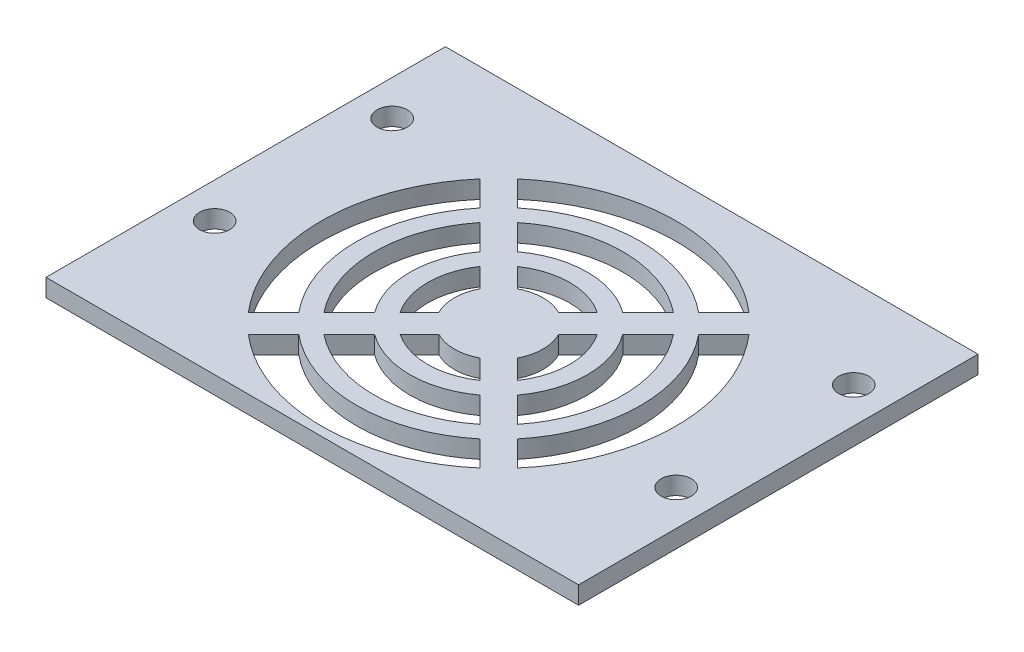
SolidWorks part; units mm, degrees
material "ABS PC"
ref_plane "Front Plane" through (0, 0, 0) normal (0, 0, 1) x (1, 0, 0)
ref_plane "Top Plane" through (0, 0, 0) normal (0, 1, 0) x (1, 0, 0)
ref_plane "Right Plane" through (0, 0, 0) normal (1, 0, 0) x (0, 0, -1)
sketch "Sketch1" plane through (0, 0, 0) normal (0, 1, 0) x (1, 0, 0)
  line L0 (0, 0) -> (0, 45)
  line L1 (0, 0) -> (60, 0)
  line L2 (0, 45) -> (60, 45)
  line L3 (60, 0) -> (60, 45)
  dimension "D1" = 60
  dimension "D2" = 45
extrude "Boss-Extrude1" add sketch "Sketch1" along normal blind 2
hole_wizard "Ø3.4 (3.4) Diameter Hole1" positions "Sketch3" profile "Sketch2" hole size "Ø3.4" standard "ANSI Metric" end condition through all
sketch "Sketch3" plane through (0, 2, 0) normal (0, 1, 0) x (1, 0, 0)
  line L0 (0, 0) -> (60, 0) construction
  line L6 (0, 45) -> (0, 0) construction
  line L7 (60, 0) -> (60, 45) construction
  point P0 (4, 15)
  point P2 (4, 35)
  point P4 (56, 35)
  point P6 (56, 15)
  dimension "D1" = 15
  dimension "D2" = 20
  dimension "D3" = 4
  dimension "D4" = 4
sketch "Sketch2" plane through (4, 2, -15) normal (1, 0, 0) x (0, 0, 1)
  line L0 (0, 0) -> (0, 2)
  line L1 (0, 2) -> (1.7, 2)
  line L2 (1.7, 2) -> (1.7, 0)
  line L5 (1.7, 0) -> (0, 0)
  line L11 (0, -6.35) -> (0, 107.95) construction
  dimension "Thru Hole Dia." = 3.4
  dimension "Thru Hole Depth" = 2
sketch "Sketch5" plane through (0, 2, 0) normal (0, 1, 0) x (1, 0, 0)
  line L1 (0, 0) -> (60, 0) construction
  line L2 (60, 45) -> (0, 45) construction
  line L3 (60, 0) -> (60, 45) construction
  line L5 (60, 45) -> (0, 45) construction
  line L6 (21.2182, 31.9032) -> (24.0696, 29.0517)
  line L9 (25.5041, 27.6172) -> (27.688, 25.4333)
  line L11 (32.312, 25.4333) -> (34.4959, 27.6172)
  line L12 (35.9304, 29.0517) -> (38.7818, 31.9032)
  line L13 (40.2032, 33.3245) -> (43.0416, 36.163)
  line L14 (16.9584, 36.163) -> (19.7968, 33.3245)
  circle A0 centre (30, 21) radius 2.5
  arc A1 (27.688, 25.4333) -> (32.312, 25.4333) centre (30, 21) cw
  arc A2 (25.5041, 27.6172) -> (34.4959, 27.6172) centre (30, 21) cw
  arc A3 (35.9304, 29.0517) -> (24.0696, 29.0517) centre (30, 21) ccw
  arc A4 (21.2182, 31.9032) -> (38.7818, 31.9032) centre (30, 21) cw
  arc A5 (19.7968, 33.3245) -> (40.2032, 33.3245) centre (30, 21) cw
  arc A6 (16.9584, 36.163) -> (43.0416, 36.163) centre (30, 21) cw
  point P2 (30, 45)
  point P10 (30, 45)
  dimension "D3" = 30
  dimension "D4" = 5
  dimension "D5" = 8
  dimension "D6" = 10
  dimension "D7" = 14
  dimension "D8" = 16
  dimension "D9" = 20
  dimension "D12" = 5
  dimension "D1" = 13.0416
  dimension "D2" = 21
  dimension "D10" = 13.0416
  dimension "D11" = 2.8384
extrude "Air holes" cut sketch "Sketch5" against normal through all
pattern_circular "CirPattern1" count 4 every 90 about axis through (30, 0, -21) along (0, 1, 0) of "Air holes"
sketch "Sketch6" plane through (0, 2, 0) normal (0, 1, 0) x (1, 0, 0)
  circle A0 centre (30, 21) radius 2.5
extrude "Boss-Extrude3" add sketch "Sketch6" against normal blind 2
